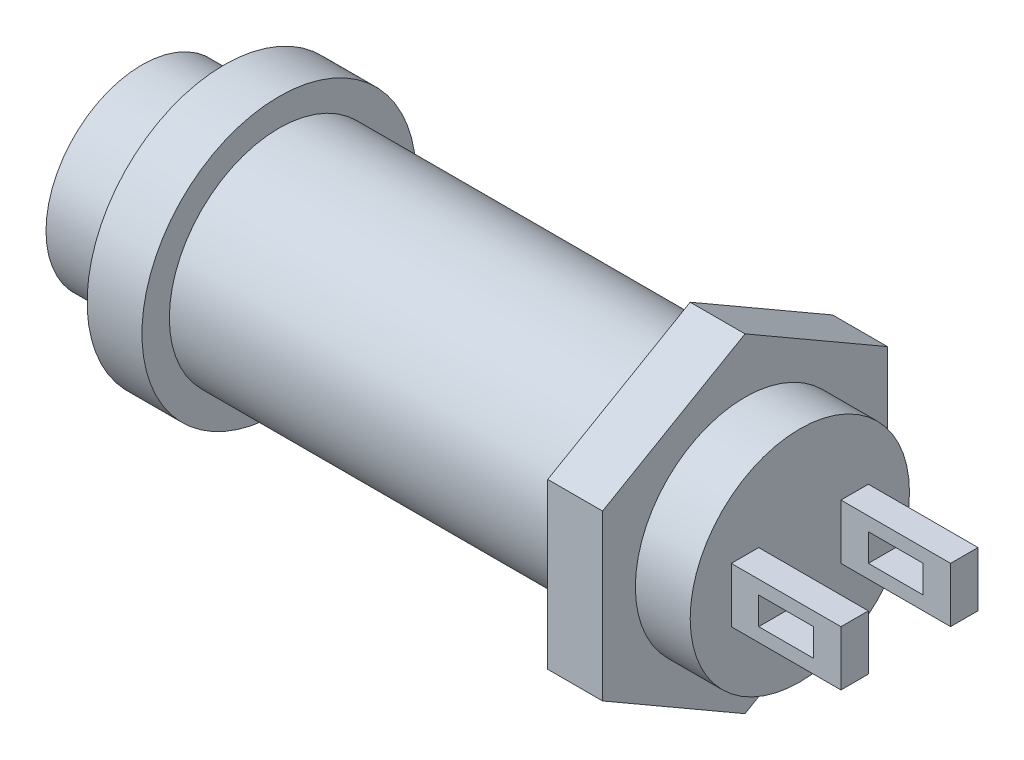
SolidWorks part; units mm, degrees
ref_plane "Alzado" through (0, 0, 0) normal (0, 0, 1) x (1, 0, 0)
ref_plane "Planta" through (0, 0, 0) normal (0, 1, 0) x (1, 0, 0)
ref_plane "Vista lateral" through (0, 0, 0) normal (1, 0, 0) x (0, 0, -1)
sketch "Croquis1" plane through (0, 0, 0) normal (0, 0, 1) x (1, 0, 0)
  line L0 (0, 0) -> (0, 0.5)
  line L1 (0, 0.5) -> (10, 0.5)
  line L2 (10, 0.5) -> (10, 2.5)
  line L3 (10, 2.5) -> (0, 2.5)
  line L4 (0, 2.5) -> (0, 3.5)
  line L5 (0, 3.5) -> (3, 3.5)
  line L6 (3, 3.5) -> (3, 5)
  line L7 (3, 5) -> (5, 5)
  line L8 (5, 5) -> (5, 4)
  line L9 (5, 4) -> (20, 4)
  line L10 (20, 4) -> (20, 6)
  line L11 (20, 6) -> (22, 6)
  line L12 (22, 6) -> (22, 4)
  line L13 (22, 4) -> (24, 4)
  line L14 (24, 4) -> (24, 0)
  line L15 (24, 0) -> (0, 0)
  dimension "D1" = 15
  dimension "D2" = 2
  dimension "D3" = 2
revolve "Revolución1" add sketch "Croquis1" angle 360 about L15
sketch "Croquis2" plane through (22, 0, 0) normal (1, 0, 0) x (0, 0, -1)
  line L1 (0, 6) -> (-5.1962, 3)
  line L2 (-5.1962, 3) -> (-5.1962, -3)
  line L3 (-5.1962, -3) -> (0, -6)
  line L4 (0, -6) -> (5.1962, -3)
  line L5 (5.1962, -3) -> (5.1962, 3)
  line L6 (5.1962, 3) -> (0, 6)
  circle A0 centre (0, 0) radius 5.1962 construction
  circle A1 centre (0, 0) radius 6
  circle M1 centre (0, 0) radius 6
extrude "Cortar-Extruir2" cut sketch "Croquis2" against normal blind 2 contours L1 M1 | L6 M1 | L5 M1 | L4 M1 | L3 M1 | L2 M1 | A1
sketch "Croquis3" plane through (24, 0, 0) normal (1, 0, 0) x (0, 0, -1)
  line L1 (-4, 0) -> (4, 0)
  line L5 (2, 2) -> (2, -2)
  line L6 (-2, 2) -> (-2, -2)
  line L8 (-2.5, -1.0012) -> (-1.5, -1.0012)
  line L9 (-2.5, -1.0012) -> (-2.5, 0.9988)
  line L10 (-2.5, 0.9988) -> (-1.5, 0.9988)
  line L11 (-1.5, -1.0012) -> (-1.5, 0.9988)
  line L12 (-2.5, -1.0012) -> (-1.5, 0.9988) construction
  line L13 (-2.5, 0.9988) -> (-1.5, -1.0012) construction
  line L14 (1.5, -1) -> (2.5, -1)
  line L15 (1.5, -1) -> (1.5, 1)
  line L16 (1.5, 1) -> (2.5, 1)
  line L17 (2.5, -1) -> (2.5, 1)
  line L18 (1.5, -1) -> (2.5, 1) construction
  line L19 (1.5, 1) -> (2.5, -1) construction
  circle A2 centre (0, 0) radius 4 construction
  circle A3 centre (0, 0) radius 4 construction
  point P6 (-2, -0.0012)
  point P18 (2, 0)
extrude "Saliente-Extruir1" add sketch "Croquis3" along normal blind 4 contours L10 L11 L8 L9 | L16 L17 L14 L15
sketch "Croquis5" plane through (0, 0, -2.5) normal (0, 0, -1) x (-1, 0, 0)
  line L0 (-24, 0) -> (-26, 0)
  line L2 (-27, -0.5) -> (-25, -0.5)
  line L3 (-24, -1) -> (-24, 1) construction
  line L4 (-27, -0.5) -> (-27, 0.5)
  line L5 (-27, 0.5) -> (-25, 0.5)
  line L6 (-25, -0.5) -> (-25, 0.5)
  line L7 (-27, -0.5) -> (-25, 0.5) construction
  line L8 (-27, 0.5) -> (-25, -0.5) construction
  dimension "D1" = 2
extrude "Cortar-Extruir3" cut sketch "Croquis5" against normal blind 10 contours L5 L6 L2 L4
